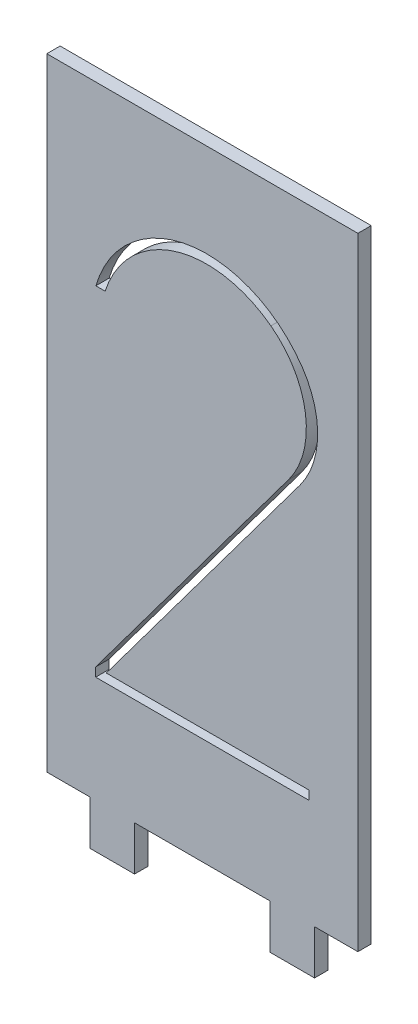
SolidWorks part; units mm, degrees
material "Glas"
ref_plane "Ebene vorne" through (0, 0, 0) normal (0, 0, 1) x (1, 0, 0)
ref_plane "Ebene oben" through (0, 0, 0) normal (0, 1, 0) x (1, 0, 0)
ref_plane "Ebene rechts" through (0, 0, 0) normal (1, 0, 0) x (0, 0, -1)
sketch "Skizze1" plane through (0, 0, 0) normal (0, 0, 1) x (1, 0, 0)
  line L1 (0, 0) -> (35, 0)
  line L2 (0, 0) -> (0, 75)
  line L3 (0, 75) -> (35, 75)
  line L4 (35, 0) -> (35, 75)
  dimension "D1" = 35
  dimension "D2" = 75
extrude "Aufsatz-Linear austragen1" add sketch "Skizze1" along normal blind 1.5
sketch "Skizze3" plane through (0, 0, 1.5) normal (0, 0, 1) x (1, 0, 0)
  line L0 (0, 0) -> (35, 0) construction
  line L1 (9.875, 0) -> (25.125, 0)
  line L2 (9.875, 0) -> (9.875, 5)
  line L3 (9.875, 5) -> (25.125, 5)
  line L4 (25.125, 0) -> (25.125, 5)
  line L5 (35, 0) -> (35, 75) construction
  line L6 (30.125, 5) -> (35, 5)
  line L7 (30.125, 5) -> (30.125, 0)
  line L8 (30.125, 0) -> (35, 0)
  line L9 (35, 5) -> (35, 0)
  line L10 (4.875, 5) -> (0, 5)
  line L11 (4.875, 5) -> (4.875, 0)
  line L12 (4.875, 0) -> (0, 0)
  line L13 (0, 5) -> (0, 0)
  dimension "D1" = 4.875
  dimension "D2" = 4.875
  dimension "D3" = 0
  dimension "D4" = 5
  dimension "D5" = 5
  dimension "D6" = 5
  dimension "D7" = 5
extrude "Schnitt-Linear austragen12" cut sketch "Skizze3" against normal blind 20
sketch "Skizze7" plane through (0, 0, 1.5) normal (0, 0, 1) x (1, 0, 0)
  line L0 (29.9809, 50.8231) -> (5.5, 18)
  line L1 (5.5, 18) -> (5.5, 17)
  line L2 (5.5, 17) -> (29.5, 17)
  line L3 (29.5, 17) -> (29.5, 18)
  line L4 (29.5, 18) -> (6.7, 18)
  line L5 (6.7, 18) -> (30.9639, 50.5322)
  line L6 (6.5662, 55.1426) -> (5.5208, 55.1426)
  line L7 (35, 5) -> (35, 75) construction
  line L8 (35, 75) -> (0, 75) construction
  line L9 (25.125, 5) -> (9.875, 5) construction
  line L10 (0, 75) -> (0, 5) construction
  arc A0 (5.5208, 55.1426) -> (30.9639, 50.5322) centre (18, 51.5) cw
  arc A1 (6.5662, 55.1426) -> (29.9809, 50.8231) centre (18, 51.5) cw
  dimension "D1" = 12
  dimension "D2" = 17
  dimension "13" = 13
  dimension "D3" = 23.5
  dimension "D4" = 12
  dimension "D5" = 1.2
  dimension "D6" = 1
  dimension "D7" = 5.5
  dimension "D8" = 5.5
extrude "Schnitt-Linear austragen14" cut sketch "Skizze7" against normal blind 1.5
fillet "Verrundung1" radius 10 1 edges at (30.9639, 50.5322, 0.75)
fillet "Verrundung2" radius 10 1 edges at (29.9809, 50.8231, 0.75)
